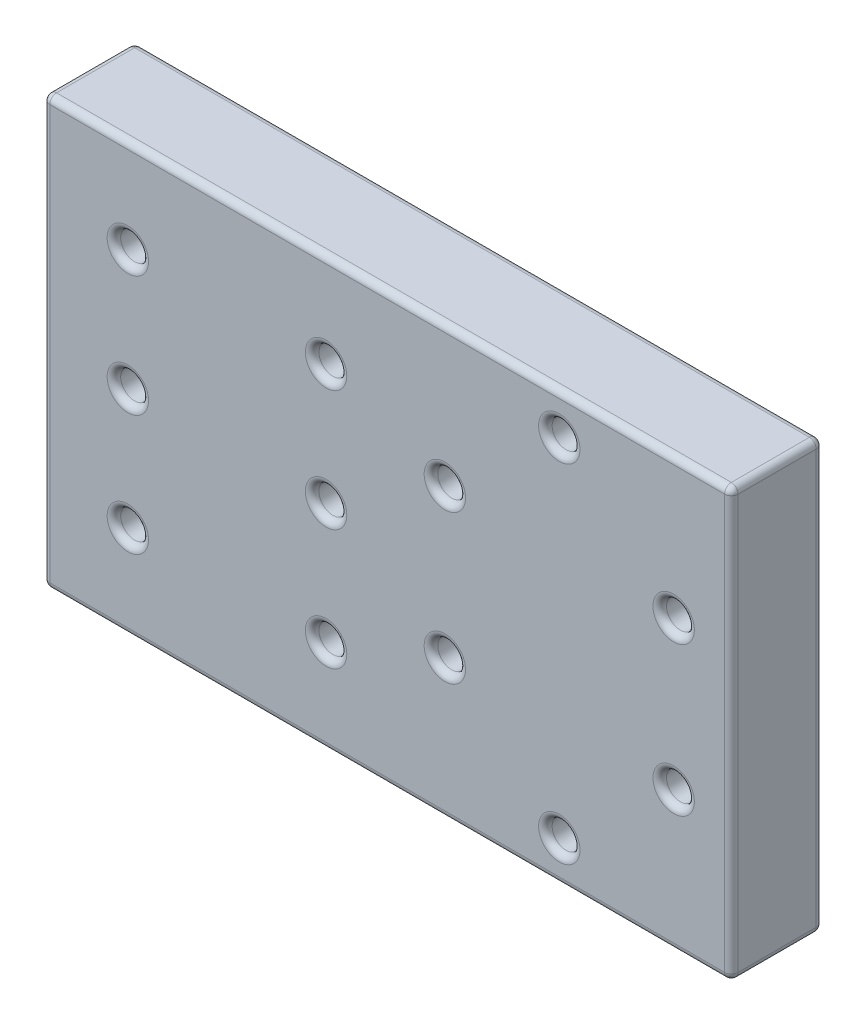
SolidWorks part; units mm, degrees
ref_plane "정면" through (0, 0, 0) normal (0, 0, 1) x (1, 0, 0)
ref_plane "윗면" through (0, 0, 0) normal (0, 1, 0) x (1, 0, 0)
ref_plane "우측면" through (0, 0, 0) normal (1, 0, 0) x (0, 0, -1)
sketch "스케치1" plane through (0, 0, 0) normal (0, 0, 1) x (1, 0, 0)
  line L1 (-50.7, 31.5) -> (50.7, 31.5)
  line L2 (-50.7, 31.5) -> (-50.7, -31.5)
  line L3 (-50.7, -31.5) -> (50.7, -31.5)
  line L4 (50.7, 31.5) -> (50.7, -31.5)
  point P4 (0, 31.5)
  point P6 (50.7, 0)
  dimension "D1" = 101.4
  dimension "D2" = 63
extrude "보스-돌출1" add sketch "스케치1" along normal blind 13.5
sketch "스케치2" plane through (0, 0, 13.5) normal (0, 0, 1) x (1, 0, 0)
  line L0 (-38.2, 17.75) -> (-9, 17.75) construction
  line L1 (-9, 17.75) -> (-9, -17.75) construction
  line L2 (-9, -17.75) -> (-38.2, -17.75) construction
  line L3 (-38.2, -17.75) -> (-38.2, 17.75) construction
  line L4 (8.5, -10.95) -> (42.2, -10.95) construction
  line L5 (42.2, -10.95) -> (42.2, 10.95) construction
  line L6 (42.2, 10.95) -> (8.5, 10.95) construction
  line L7 (8.5, 10.95) -> (8.5, -10.95) construction
  line L8 (8.5, 0) -> (42.2, 0) construction
  line L9 (25.35, 25.55) -> (25.35, -25.55) construction
  line L10 (-50.7, 31.5) -> (-50.7, -31.5) construction
  line L11 (50.7, -31.5) -> (50.7, 31.5) construction
  circle A0 centre (-38.2, 17.75) radius 2.05
  circle A1 centre (-38.2, 0) radius 2.05
  circle A2 centre (-38.2, -17.75) radius 2.05
  circle A3 centre (-9, 17.75) radius 2.05
  circle A4 centre (-9, 0) radius 2.05
  circle A5 centre (-9, -17.75) radius 2.05
  circle A6 centre (25.35, 25.55) radius 2.05
  circle A7 centre (8.5, 10.95) radius 2.05
  circle A8 centre (8.5, -10.95) radius 2.05
  circle A9 centre (42.2, 10.95) radius 2.05
  circle A10 centre (42.2, -10.95) radius 2.05
  circle A11 centre (25.35, -25.55) radius 2.05
  point P25 (-38.2, 0)
  point P27 (-9, 0)
  point P28 (25.35, 0)
  dimension "D1" = 4.1
  dimension "D2" = 35.5
  dimension "D3" = 29.2
  dimension "D4" = 12.5
  dimension "D5" = 33.7
  dimension "D6" = 21.9
  dimension "D7" = 51.1
  dimension "D8" = 8.5
extrude "컷-돌출1" cut sketch "스케치2" against normal through all
fillet "필렛1" radius 1 36 edges at (-50.7, -31.5, 6.75) (50.7, -31.5, 6.75) (50.7, 31.5, 6.75) (-50.7, 31.5, 6.75) (0, -31.5, 0) (50.7, 0, 0) (0, 31.5, 0) (-50.7, 0, 0) (-36.15, 17.75, 0) (27.4, 25.55, 0) (10.55, 10.95, 0) (10.55, -10.95, 0) (44.25, 10.95, 0) (44.25, -10.95, 0) (27.4, -25.55, 0) (-6.95, -17.75, 0) (-6.95, 0, 0) (-6.95, 17.75, 0) (-36.15, -17.75, 0) (-36.15, 0, 0) (0, 31.5, 13.5) (50.7, 0, 13.5) (0, -31.5, 13.5) (-50.7, 0, 13.5) (-36.15, 17.75, 13.5) (27.4, 25.55, 13.5) (10.55, 10.95, 13.5) (10.55, -10.95, 13.5) (44.25, 10.95, 13.5) (44.25, -10.95, 13.5) (27.4, -25.55, 13.5) (-6.95, -17.75, 13.5) (-6.95, 0, 13.5) (-6.95, 17.75, 13.5) (-36.15, -17.75, 13.5) (-36.15, 0, 13.5)
